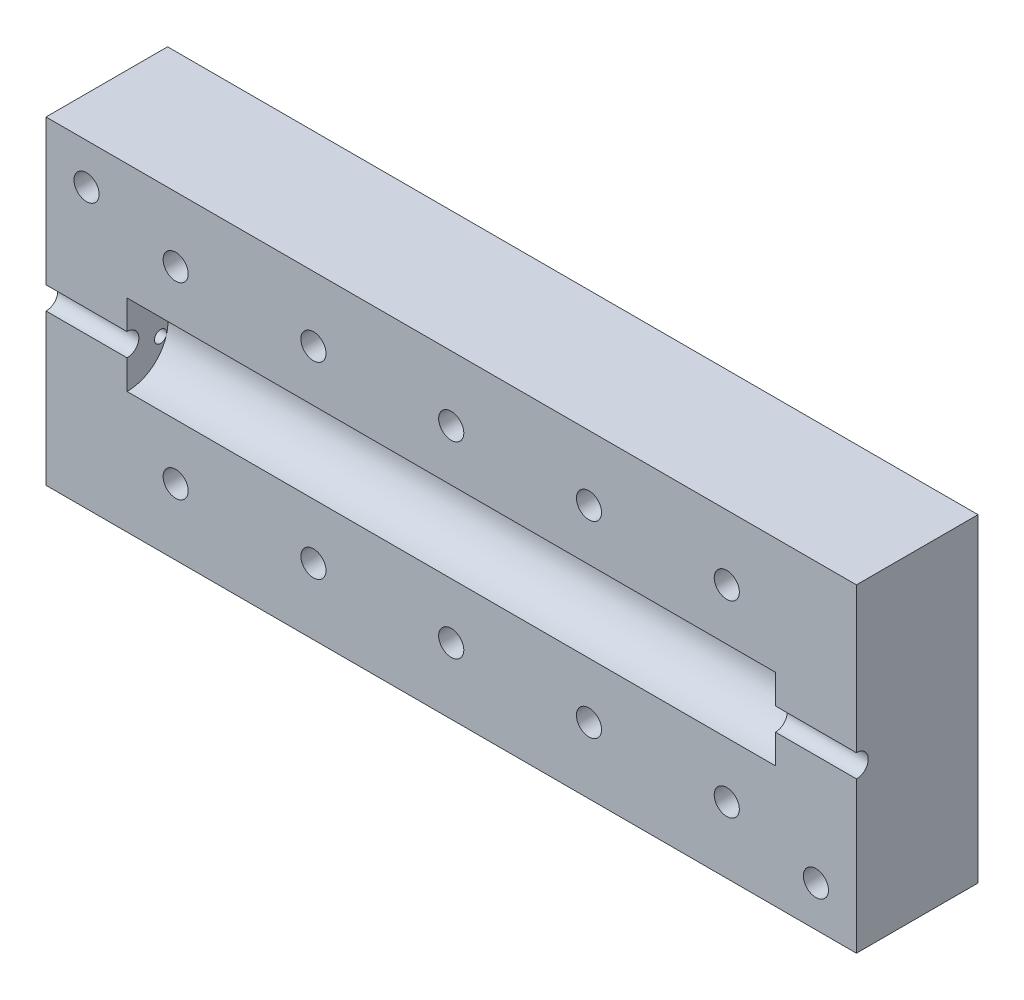
SolidWorks part; units mm, degrees
ref_plane "Ebene vorne" through (0, 0, 0) normal (0, 0, 1) x (1, 0, 0)
ref_plane "Ebene oben" through (0, 0, 0) normal (0, 1, 0) x (1, 0, 0)
ref_plane "Ebene rechts" through (0, 0, 0) normal (1, 0, 0) x (0, 0, -1)
sketch "Skizze2" plane through (0, 0, 0) normal (0, 0, 1) x (1, 0, 0)
  line L1 (0, 0) -> (100, 0)
  line L2 (0, 0) -> (0, 39.3642)
  line L3 (0, 39.3642) -> (100, 39.3642)
  line L4 (100, 0) -> (100, 39.3642)
  dimension "D1" = 39.3642
  dimension "D2" = 100
extrude "Aufsatz-Linear austragen1" add sketch "Skizze2" along normal blind 30
sketch "Skizze3" plane through (0, 0, 30) normal (0, 0, 1) x (1, 0, 0)
  line L0 (0, 19.6821) -> (100, 19.6821) construction
  line L1 (0, 39.3642) -> (0, 0) construction
  line L2 (100, 0) -> (100, 39.3642) construction
ref_plane "Ebene2" through (0, 19.7642, 0) normal (0, 1, 0) x (1, 0, 0)
sketch "Skizze9" plane through (0, 0, 30) normal (0, 0, 1) x (1, 0, 0)
  line L0 (50, 0) -> (50, 39.3642) construction
  line L1 (0, 0) -> (100, 0) construction
  line L2 (100, 39.3642) -> (0, 39.3642) construction
ref_plane "Ebene3" through (50, 0, 0) normal (-1, 0, 0) x (0, 0, 1)
sketch "Skizze10" plane through (50, 0, 0) normal (-1, 0, 0) x (0, 0, 1)
  line L0 (14.9458, 42.0451) -> (14.9458, -1.991) construction
  line L1 (-1.6741, 19.9497) -> (31.3778, 19.9497) construction
  circle A0 centre (14.9458, 20.027) radius 5
  dimension "D1" = 10
extrude "Schnitt-Linear austragen1" cut sketch "Skizze10" against normal blind 40 and the other way blind 40
ref_plane "Ebene4" through (90, 0, 0) normal (-1, 0, 0) x (0, 0, 1)
ref_plane "Ebene5" through (10, 0, 0) normal (-1, 0, 0) x (0, 0, 1)
sketch "Skizze17" plane through (90, 0, 0) normal (-1, 0, 0) x (0, 0, 1)
  circle A0 centre (14.9458, 20.027) radius 1.4
  dimension "D1" = 2.8
extrude "Schnitt-Linear austragen2" cut sketch "Skizze17" against normal through all
mirror "Spiegeln1" about plane through (50, 0, 0) normal (-1, 0, 0) of "Schnitt-Linear austragen2"
sketch "Skizze18" plane through (0, 39.3642, 0) normal (0, 1, 0) x (1, 0, 0)
  line L0 (100, -15) -> (0, -15) construction
  line L1 (100, -30) -> (100, 0) construction
ref_plane "Ebene6" through (0, 0, 15) normal (0, 0, -1) x (-1, 0, 0)
sketch "Skizze24" plane through (0, 0, 30) normal (0, 0, 1) x (1, 0, 0)
  line L0 (0, 39.3642) -> (0, 0) construction
  line L1 (100, 39.3642) -> (0, 39.3642) construction
  line L4 (100, 0) -> (100, 39.3642) construction
  circle A0 centre (16, 31.3642) radius 1.55
  circle A1 centre (33, 31.3642) radius 1.55
  circle A2 centre (50, 31.3642) radius 1.55
  circle A3 centre (67, 31.3642) radius 1.55
  circle A4 centre (84, 31.3642) radius 1.55
  dimension "D1" = 3.1
  dimension "D4" = 3.1
  dimension "D5" = 3.1
  dimension "D6" = 3.1
  dimension "D7" = 3.1
  dimension "D2" = 16
  dimension "D3" = 8
  dimension "D8" = 17
  dimension "D9" = 17
  dimension "D10" = 17
  dimension "D11" = 17
  dimension "D12" = 16
extrude "Schnitt-Linear austragen4" cut sketch "Skizze24" against normal through all
sketch "Skizze22" plane through (0, 0, 0) normal (-1, 0, 0) x (0, 0, 1)
  line L0 (30, 39.3642) -> (0, 39.3642) construction
  line L1 (0, 0) -> (15, 0)
  line L2 (0, 0) -> (0, 39.3642)
  line L3 (0, 39.3642) -> (15, 39.3642)
ref_plane "Ebene7" through (0, 0, 8.4) normal (0, 0, -1) x (-1, 0, 0)
ref_plane "Ebene8" through (16, 0, 0) normal (-1, 0, 0) x (0, 0, 1)
sketch "Skizze35" plane through (0, 0, 30) normal (0, 0, 1) x (1, 0, 0)
  line L0 (89.9018, 21.3451) -> (89.9018, 39.3769) construction
  line L1 (89.9018, 39.3769) -> (89.9018, 0) construction
  line L2 (0, 0) -> (100, 0) construction
ref_plane "Ebene9" through (90, 0, 0) normal (1, 0, 0) x (0, 0, -1)
sketch "Skizze36" plane through (90, 0, 0) normal (1, 0, 0) x (0, 0, -1)
  line L0 (-20.1004, 18.2046) -> (-18.9246, 18.6336)
  circle A0 centre (-18.9246, 18.6336) radius 0.75
  point P3 (-19.5125, 18.4191)
  dimension "D1" = 1.5
sketch "Skizze37" plane through (100, 0, 0) normal (1, 0, 0) x (0, 0, -1)
  circle A0 centre (-18.9246, 18.6336) radius 0.7369
extrude "Schnitt-Linear austragen9" cut sketch "Skizze37" against normal through all
sketch "Skizze40" plane through (100, 0, 0) normal (1, 0, 0) x (0, 0, -1)
  circle A0 centre (-18.9246, 18.6336) radius 2.1
  dimension "D1" = 4.2
extrude "Schnitt-Linear austragen10" cut sketch "Skizze40" against normal blind 6
sketch "Skizze42" plane through (0, 0, 0) normal (-1, 0, 0) x (0, 0, 1)
  line L0 (10.1439, 18.6336) -> (10.8642, 18.8426) construction
  circle A0 centre (14.9458, 20.027) radius 5 construction
  circle A1 centre (10.8642, 18.8426) radius 0.75
  dimension "D1" = 0.75
extrude "Schnitt-Linear austragen12" cut sketch "Skizze42" against normal blind 10
fillet "Verrundung1" radius 1 1 edges at (94, 18.6336, 18.1877)
sketch "Skizze46" plane through (0, 0, 0) normal (0, 0, -1) x (-1, 0, 0)
  circle A0 centre (-84, 31.3642) radius 2.85
  dimension "D1" = 5.7
extrude "Schnitt-Linear austragen15" cut sketch "Skizze46" against normal blind 10
sketch "Skizze50" plane through (0, 0, 30) normal (0, 0, 1) x (1, 0, 0)
  line L0 (81.15, 33.0096) -> (81.15, 39.3642)
  line L2 (81.15, 33.0096) -> (81.15, 29.7187)
  line L3 (81.15, 29.7187) -> (84, 28.0733)
  line L4 (84, 28.0733) -> (86.85, 29.7187)
  line L5 (86.85, 29.7187) -> (86.85, 33.0096)
  line L7 (100, 39.3642) -> (0, 39.3642) construction
  line L8 (81.15, 39.3642) -> (86.85, 39.3642)
  line L9 (86.85, 39.3642) -> (86.85, 33.0096)
  line L11 (84, 34.6551) -> (81.15, 33.0096) [skipped]
  line L12 (86.85, 33.0096) -> (84, 34.6551) [skipped]
  circle A0 centre (84, 31.3642) radius 2.85 construction
  dimension "D1" = 5.7
extrude "Schnitt-Linear austragen25" cut sketch "Skizze50" against normal blind 2.7 from offset 5 offset against normal yes
pattern_linear "Lineares Muster1" count 5 spacing 17 along (-1, 0, 0) of "Schnitt-Linear austragen25", "Schnitt-Linear austragen15"
mirror "Spiegeln2" about plane through (0, 19.7642, 0) normal (0, 1, 0) of "Lineares Muster1", "Schnitt-Linear austragen15", "Schnitt-Linear austragen25"
mirror "Spiegeln3" about plane through (0, 19.7642, 0) normal (0, 1, 0) of "Schnitt-Linear austragen4"
sketch "Skizze51" plane through (0, 0, 30) normal (0, 0, 1) x (1, 0, 0)
  line L0 (100, 0) -> (100, 39.3642) construction
  line L1 (0, 0) -> (100, 0) construction
  line L2 (0, 0) -> (0, 39.3642) construction
  line L3 (100, 39.3642) -> (0, 39.3642) construction
  circle A0 centre (5, 34.3642) radius 1.55
  circle A1 centre (95, 5) radius 1.55
  dimension "D1" = 3.1
  dimension "D2" = 3.1
  dimension "D3" = 5
  dimension "D4" = 5
  dimension "D5" = 5
  dimension "D6" = 5
extrude "Schnitt-Linear austragen26" cut sketch "Skizze51" against normal blind 10 from offset 10 offset against normal yes
sketch "Skizze45" plane through (100, 0, 0) normal (1, 0, 0) x (0, 0, -1)
  line L1 (-15, 39.3642) -> (0, 39.3642)
  line L2 (-15, 39.3642) -> (-15, 0)
  line L3 (-15, 0) -> (0, 0)
  line L4 (0, 39.3642) -> (0, 0)
sketch "Skizze52" plane through (0, 0, 0) normal (-1, 0, 0) x (0, 0, 1)
  line L0 (30, 0) -> (30, 39.3642) construction
  line L1 (15, 0) -> (30, 0)
  line L2 (15, 0) -> (15, 39.3642)
  line L3 (15, 39.3642) -> (30, 39.3642)
  line L4 (30, 0) -> (30, 39.3642)
  line L5 (30, 39.3642) -> (0, 39.3642) construction
extrude "Schnitt-Linear austragen27" cut sketch "Skizze52" against normal through all
